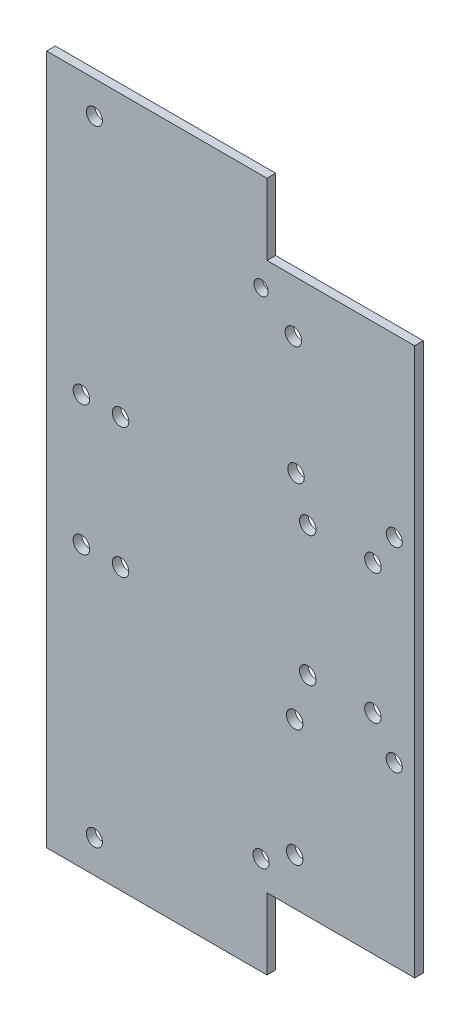
SolidWorks part; units mm, degrees
material "Thornel Mat VMA"
ref_plane "Front Plane" through (0, 0, 0) normal (0, 0, 1) x (1, 0, 0)
ref_plane "Top Plane" through (0, 0, 0) normal (0, 1, 0) x (1, 0, 0)
ref_plane "Right Plane" through (0, 0, 0) normal (1, 0, 0) x (0, 0, -1)
sketch "Sketch2" plane through (0, 0, 0) normal (0, 0, 1) x (-1, 0, 0)
  line L11 (-2.9301, 168.7083) -> (38.7094, 168.7083)
  line L12 (-2.9301, 8.6883) -> (38.7094, 8.6883)
  line L13 (38.7094, -12.1397) -> (38.7094, 8.6883)
  line L14 (143.4971, -12.1397) -> (38.7094, -12.1397)
  line L15 (38.7094, 189.5363) -> (38.7094, 168.7083)
  line L16 (143.4971, 189.5363) -> (38.7094, 189.5363)
  line L17 (104.6174, 110.8598) -> (143.4971, 189.5363)
  line L18 (104.6174, 66.5368) -> (143.4971, -12.1397)
  line L19 (104.6174, 66.5368) -> (72.8674, 66.5368)
  line L20 (72.8674, 66.5368) -> (72.8674, 110.8598)
  line L21 (104.6174, 110.8598) -> (72.8674, 110.8598)
  line L22 (-2.9301, 168.7083) -> (-2.9301, 8.6883)
  line L23 (41.9566, 19.6103) -> (41.9566, 13.2603) construction
  circle A0 centre (41.9566, 160.9613) radius 2.3495
  circle A1 centre (90.6739, 180.0113) radius 2.3495
  circle A2 centre (90.6739, -2.6147) radius 2.3495
  circle A3 centre (3.0351, 117.2098) radius 2.3495
  circle A4 centre (3.0351, 60.1868) radius 2.3495
  circle A5 centre (41.9566, 16.4353) radius 2.0955
  point P36 (41.9566, 16.4353)
  dimension "D3" = 4.699
  dimension "D7" = 31.75
  dimension "D8" = 41.6395
  dimension "D9" = 20.828
  dimension "D10" = 160.02
  dimension "D11" = 20.828
  dimension "D12" = 41.6395
  dimension "D13" = 104.7876
  dimension "D14" = 116.297
  dimension "D15" = 116.297
  dimension "D16" = 44.323
  dimension "D17" = 26.297
  dimension "D18" = 9.525
  dimension "D19" = 28.575
  dimension "D20" = 7.747
  dimension "D21" = 51.9645
  dimension "D22" = 51.4985
  dimension "D23" = 5.9651
  dimension "D24" = 51.4985
  dimension "D25" = 5.9651
  dimension "D26" = 7.747
  dimension "D27" = 3.2471
  dimension "D28" = 9.525
  dimension "D29" = 51.9645
extrude "Boss-Extrude1" add sketch "Sketch2" along normal blind 2.54
sketch "Sketch3" plane through (0, 0, 2.54) normal (0, 0, 1) x (1, 0, 0)
  line L1 (-104.6174, -66.5368) -> (-72.8674, -66.5368)
  line L2 (-104.6174, -66.5368) -> (-104.6174, -110.8598)
  line L3 (-104.6174, -110.8598) -> (-72.8674, -110.8598)
  line L4 (-72.8674, -66.5368) -> (-72.8674, -110.8598)
extrude "Boss-Extrude2" add sketch "Sketch3" against normal up to surface (2.54 mm away) up to face at (-65.9118, -88.6983, 0)
sketch "Sketch4" plane through (0, 0, 2.54) normal (0, 0, 1) x (1, 0, 0)
  line L0 (-104.6174, -66.5368) -> (-104.6174, -72.8868)
  line L1 (-104.6174, -66.5368) -> (-104.6174, -110.8598) construction
  line L2 (-104.6174, -69.7118) -> (2.9301, -69.7118) construction
  line L3 (2.9301, -168.7083) -> (2.9301, -8.6883) construction
  line L4 (-104.6174, -88.6983) -> (2.9301, -88.6983) construction
  line L5 (-104.6174, -107.6848) -> (2.9301, -107.6848) construction
  line L6 (-104.6174, -110.8598) -> (-104.6174, -104.5098)
  circle A0 centre (-94.4574, -69.7118) radius 2.413
  circle A1 centre (-83.0274, -69.7118) radius 2.413
  circle A2 centre (-28.3119, -69.7118) radius 2.413
  circle A3 centre (-9.2619, -69.7118) radius 2.413
  circle A4 centre (-9.2619, -107.6848) radius 2.413
  circle A5 centre (-28.3119, -107.6848) radius 2.413
  circle A6 centre (-83.0274, -107.6848) radius 2.413
  circle A7 centre (-94.4574, -107.6848) radius 2.413
  dimension "D2" = 10.16
  dimension "D4" = 4.826
  dimension "D5" = 4.826
  dimension "D8" = 4.826
  dimension "D9" = 4.826
  dimension "D1" = 3.175
  dimension "D3" = 11.43
  dimension "D6" = 19.05
  dimension "D7" = 12.192
extrude "Cut-Extrude1" cut sketch "Sketch4" against normal through all contours A0 | A1 | A2 | A3 | A4 | A5 | A6 | A7
sketch "Sketch5" plane through (0, 0, 2.54) normal (0, 0, 1) x (1, 0, 0)
  circle A0 centre (-31.739, -58.2731) radius 2.413
  dimension "D1" = 4.826
sketch "Sketch6" plane through (0, 0, 2.54) normal (0, 0, 1) x (1, 0, 0)
  circle A0 centre (-32.5114, -23.9918) radius 2.413
  dimension "D1" = 4.826
extrude "Cut-Extrude2" cut sketch "Sketch5" against normal through all
extrude "Cut-Extrude3" cut sketch "Sketch6" against normal through all
sketch "Sketch7" plane through (0, 0, 2.54) normal (0, 0, 1) x (1, 0, 0)
  circle A0 centre (-32.1405, -155.0714) radius 2.413
  circle A1 centre (-32.1405, -120.7814) radius 2.413
  dimension "D1" = 4.826
  dimension "D2" = 4.826
extrude "Cut-Extrude4" cut sketch "Sketch7" against normal through all
sketch "Sketch8" plane through (0, 0, 2.54) normal (0, 0, 1) x (1, 0, 0)
  line L0 (-38.7094, -168.7083) -> (2.9301, -168.7083) construction
  line L1 (-32.2387, 12.4252) -> (-40.2334, 12.4252)
  line L2 (-32.2387, 12.4252) -> (-32.2387, -8.6883)
  line L3 (-32.2387, -8.6883) -> (-40.2334, -8.6883)
  line L4 (-40.2334, 12.4252) -> (-40.2334, -8.6883)
  line L5 (-18.7398, -197.6692) -> (-40.2334, -197.6692)
  line L6 (-18.7398, -197.6692) -> (-18.7398, -168.7083)
  line L7 (-18.7398, -168.7083) -> (-40.2334, -168.7083)
  line L8 (-40.2334, -197.6692) -> (-40.2334, -168.7083)
  line L13 (-38.7094, -189.5363) -> (-38.7094, -168.7083) construction
  line L14 (2.9301, -8.6883) -> (-38.7094, -8.6883) construction
  dimension "D1" = 1.524
extrude "Cut-Extrude5" cut sketch "Sketch8" against normal through all
sketch "Sketch9" plane through (0, 0, 2.54) normal (0, 0, 1) x (1, 0, 0)
  line L0 (-104.6174, -66.5368) -> (-104.6174, 15.6366)
  line L1 (-104.6174, 15.6366) -> (-183.1792, 15.6366)
  line L2 (-104.6174, -66.5368) -> (-104.6174, -202.664)
  line L3 (-104.6174, -202.664) -> (-188.2621, -199.7213)
  line L4 (-188.2621, -199.7213) -> (-183.1792, 15.6366)
extrude "Cut-Extrude6" cut sketch "Sketch9" against normal through all both
